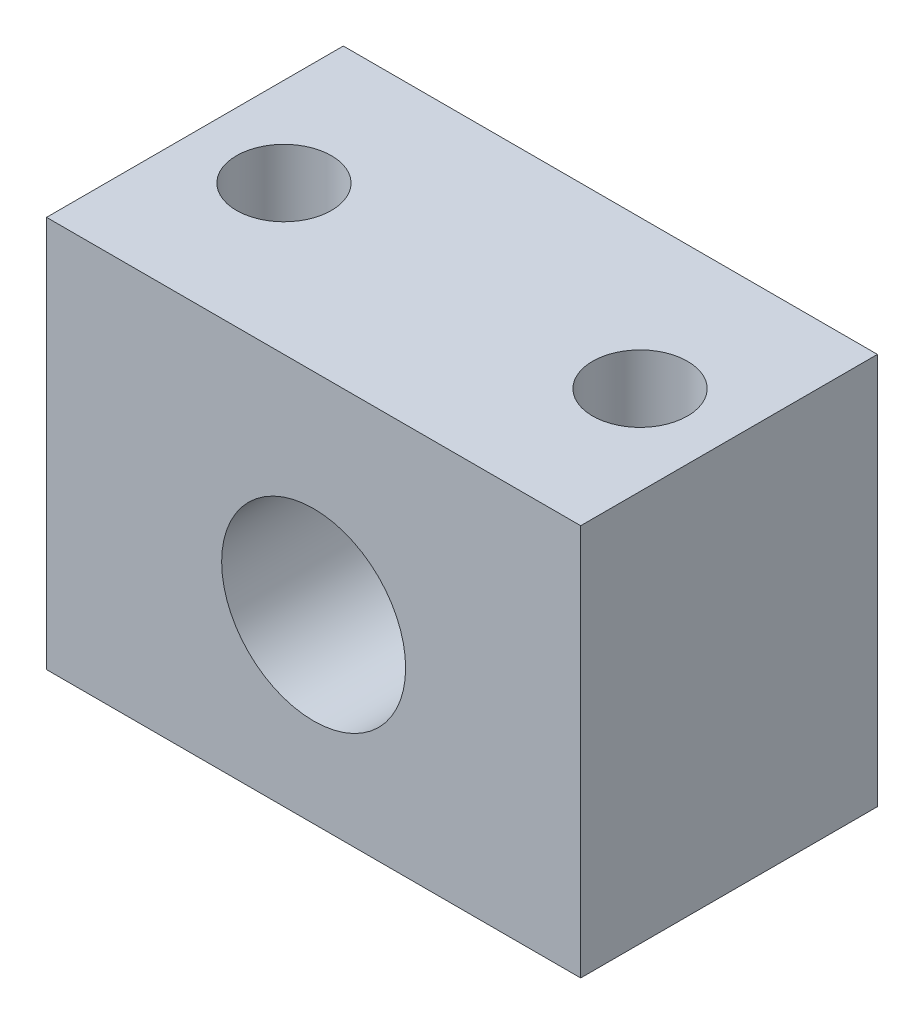
SolidWorks part; units mm, degrees
material "ABS"
ref_plane "正面" through (0, 0, 0) normal (0, 0, 1) x (1, 0, 0)
ref_plane "平面" through (0, 0, 0) normal (0, 1, 0) x (1, 0, 0)
ref_plane "右側面" through (0, 0, 0) normal (1, 0, 0) x (0, 0, -1)
sketch "ｽｹｯﾁ1" plane through (0, 0, 0) normal (0, 0, 1) x (1, 0, 0)
  line L0 (0, 0) -> (0, 0.5) construction
  line L1 (9, -6.1) -> (-9, -6.1)
  line L2 (9, -6.1) -> (9, 7.1)
  line L3 (9, 7.1) -> (-9, 7.1)
  line L4 (-9, -6.1) -> (-9, 7.1)
  line L5 (9, -6.1) -> (-9, 7.1) construction
  line L6 (9, 7.1) -> (-9, -6.1) construction
  line L7 (0, 3.1) -> (-9, 3.1) construction
  line L8 (0, -3.1) -> (-9, -3.1) construction
  circle A0 centre (0, 0) radius 3.1
  point P3 (0, 0.5)
  dimension "D1" = 6.2
  dimension "D2" = 4
  dimension "D3" = 3
  dimension "D4" = 18
extrude "ﾎﾞｽ - 押し出し1" add sketch "ｽｹｯﾁ1" along normal blind 10
sketch "ｽｹｯﾁ2" plane through (0, 7.1, 0) normal (0, 1, 0) x (1, 0, 0)
  line L0 (-3.1, -10) -> (3.1, -10) construction
  line L1 (-3.1, -10) -> (3.1, -10) construction
  line L2 (-9, -5) -> (9, -5) construction
  line L3 (-9, -10) -> (-9, 0) construction
  line L4 (9, -10) -> (9, 0) construction
  line L6 (0, 0) -> (0, -10) construction
  circle A0 centre (-6, -5) radius 1.6
  circle A1 centre (6, -5) radius 1.6
  dimension "D1" = 3.2
  dimension "D2" = 12
extrude "ｶｯﾄ - 押し出し1" cut sketch "ｽｹｯﾁ2" against normal blind 10
